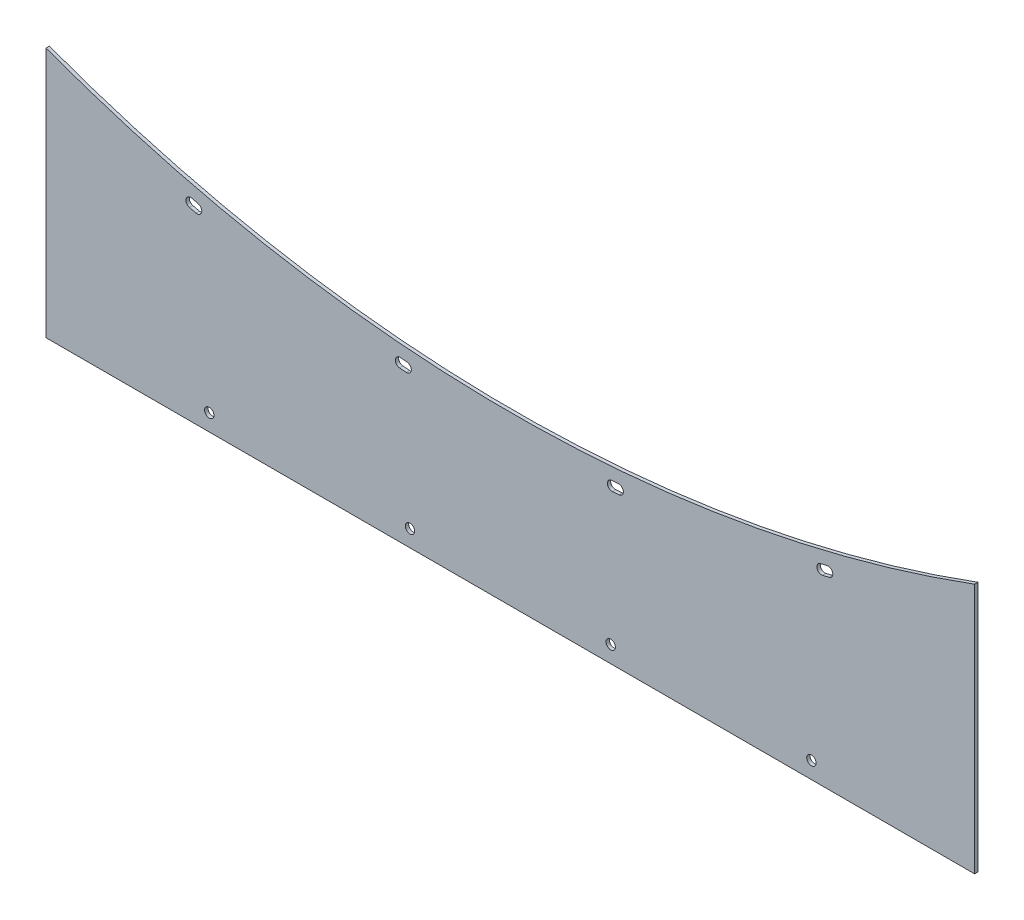
SolidWorks part; units mm, degrees
ref_plane "Front Plane" through (0, 0, 0) normal (0, 0, 1) x (1, 0, 0)
ref_plane "Top Plane" through (0, 0, 0) normal (0, 1, 0) x (1, 0, 0)
ref_plane "Right Plane" through (0, 0, 0) normal (1, 0, 0) x (0, 0, -1)
sketch "Sketch1" plane through (0, 0, 0) normal (0, 0, 1) x (1, 0, 0)
  line L0 (1651.4754, 459.3922) -> (263.4754, 459.3922)
  line L1 (263.4754, 459.3922) -> (263.4754, 834.3922)
  line L2 (1651.4754, 459.3922) -> (1651.4754, 834.3922)
  line L3 (1434.0549, 734.606) -> (1424.3295, 732.2789)
  line L4 (1421.0714, 745.8945) -> (1430.7969, 748.2217)
  line L5 (1119.9827, 684.3088) -> (1110.013, 683.5317)
  line L6 (1108.925, 697.4894) -> (1118.8947, 698.2665)
  line L7 (801.909, 683.7626) -> (791.9405, 684.5546)
  line L8 (793.0493, 698.5106) -> (803.0179, 697.7186)
  line L9 (487.6659, 732.9807) -> (477.944, 735.3224)
  line L10 (481.2224, 748.9332) -> (490.9444, 746.5914)
  arc A0 (263.4754, 834.3922) -> (1651.4754, 834.3922) centre (957.4754, 2704.7903) ccw
  circle A1 centre (507.4754, 484.3922) radius 7
  circle A2 centre (807.4754, 484.3922) radius 7
  circle A3 centre (1107.4754, 484.3922) radius 7
  circle A4 centre (1407.4754, 484.3922) radius 7
  arc A5 (1434.0549, 734.606) -> (1430.7969, 748.2217) centre (1432.4259, 741.4139) ccw
  arc A6 (1421.0714, 745.8945) -> (1424.3295, 732.2789) centre (1422.7005, 739.0867) ccw
  arc A7 (1119.9827, 684.3088) -> (1118.8947, 698.2665) centre (1119.4387, 691.2877) ccw
  arc A8 (1108.925, 697.4894) -> (1110.013, 683.5317) centre (1109.469, 690.5105) ccw
  arc A9 (801.909, 683.7626) -> (803.0179, 697.7186) centre (802.4635, 690.7406) ccw
  arc A10 (793.0493, 698.5106) -> (791.9405, 684.5546) centre (792.4949, 691.5326) ccw
  arc A11 (487.6659, 732.9807) -> (490.9444, 746.5914) centre (489.3051, 739.7861) ccw
  arc A12 (481.2224, 748.9332) -> (477.944, 735.3224) centre (479.5832, 742.1278) ccw
extrude "Boss-Extrude1" add sketch "Sketch1" along normal blind 5
